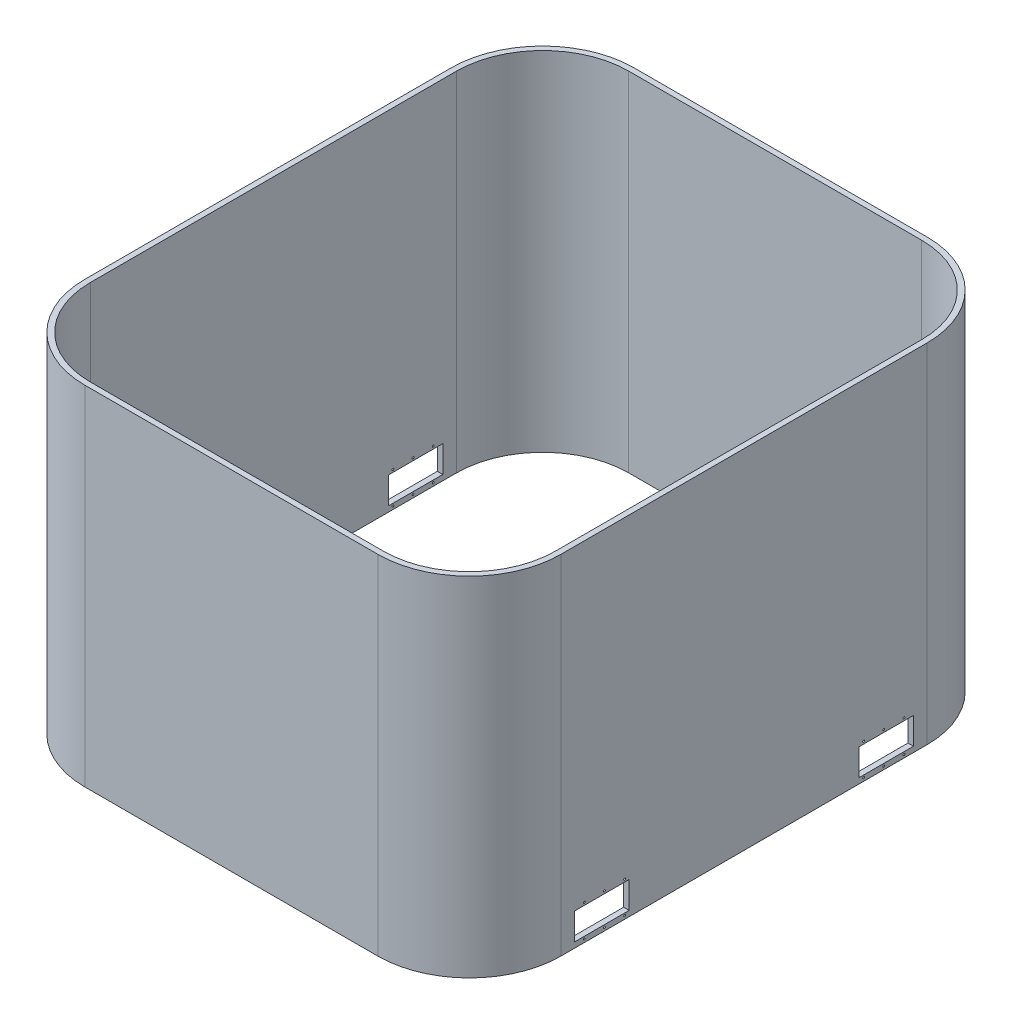
SolidWorks part; units mm, degrees
material "6063-O"
ref_plane "Plano frontal" through (0, 0, 0) normal (0, 0, 1) x (1, 0, 0)
ref_plane "Plano superior" through (0, 0, 0) normal (0, 1, 0) x (1, 0, 0)
ref_plane "Plano direito" through (0, 0, 0) normal (1, 0, 0) x (0, 0, -1)
sketch "Chapa inferior" plane through (0, 0, 0) normal (0, 1, 0) x (1, 0, 0)
  line L1 (-160, 300) -> (160, 300)
  line L2 (-260, 200) -> (-260, -200)
  line L3 (-160, -300) -> (160, -300)
  line L4 (260, 200) -> (260, -200)
  line L5 (-260, 300) -> (260, -300) construction
  line L6 (-260, -300) -> (260, 300) construction
  arc A0 (160, 300) -> (260, 200) centre (160, 200) cw
  arc A1 (160, -300) -> (260, -200) centre (160, -200) ccw
  arc A2 (-260, -200) -> (-160, -300) centre (-160, -200) ccw
  arc A3 (-160, 300) -> (-260, 200) centre (-160, 200) ccw
  point P0 (0, 0)
  dimension "D3" = 100
  dimension "D4" = 100
  dimension "D5" = 100
  dimension "D6" = 100
  dimension "D1" = 520
  dimension "D2" = 600
extrude "ChapaLateral" add sketch "Chapa inferior" along normal blind 380 thin
sketch "Esboço8" plane through (254, 0, 0) normal (-1, 0, 0) x (0, 0, 1)
  line L0 (-200, 380) -> (-200, 0) construction
  line L1 (-185, 6) -> (-125.5, 6)
  line L2 (-185, 6) -> (-185, 35.2)
  line L3 (-185, 35.2) -> (-125.5, 35.2)
  line L4 (-125.5, 6) -> (-125.5, 35.2)
  line L5 (-185, 6) -> (-125.5, 35.2) construction
  line L6 (-185, 35.2) -> (-125.5, 6) construction
  line L7 (200, 0) -> (-200, 0) construction
  point P0 (-155.25, 20.6)
  dimension "D1" = 59.5
  dimension "D2" = 15
  dimension "D3" = 29.2
  dimension "D4" = 6
sketch "Esboço10" plane through (254, 0, 0) normal (-1, 0, 0) x (0, 0, 1)
  line L1 (125.5, 6) -> (185, 6)
  line L2 (125.5, 6) -> (125.5, 35.2)
  line L3 (125.5, 35.2) -> (185, 35.2)
  line L4 (185, 6) -> (185, 35.2)
  line L5 (125.5, 6) -> (185, 35.2) construction
  line L6 (125.5, 35.2) -> (185, 6) construction
  line L8 (200, 380) -> (200, 0) construction
  line L9 (200, 0) -> (-200, 0) construction
  point P0 (155.25, 20.6)
  dimension "D1" = 59.5
  dimension "D2" = 15
  dimension "D3" = 29.2
  dimension "D4" = 6
extrude "MotorTraseiro" cut sketch "Esboço8" against normal through all both and the other way through all
extrude "MotorFrontal" cut sketch "Esboço10" against normal through all both and the other way through all
sketch "Esboço15" plane through (-260, 0, 0) normal (-1, 0, 0) x (0, 0, 1)
  line L1 (185, 6) -> (185, 35.2) construction
  line L2 (185, 35.2) -> (125.5, 35.2) construction
  line L3 (125.5, 35.2) -> (125.5, 6) construction
  line L7 (0, 0) -> (0, 380) construction
  line L8 (-200, 0) -> (200, 0) construction
  line L9 (-200, 380) -> (200, 380) construction
  circle A0 centre (174.5, 38) radius 1.025
  circle A1 centre (152.5, 38) radius 1.025
  circle A2 centre (130.5, 38) radius 1.025
  circle A3 centre (152.5, 3.4) radius 1.025
  circle A4 centre (130.5, 3.4) radius 1.025
  circle A5 centre (174.5, 3.4) radius 1.025
  circle A12 centre (-174.5, 3.4) radius 1.025
  circle A13 centre (-130.5, 3.4) radius 1.025
  circle A14 centre (-152.5, 3.4) radius 1.025
  circle A15 centre (-130.5, 38) radius 1.025
  circle A16 centre (-152.5, 38) radius 1.025
  circle A17 centre (-174.5, 38) radius 1.025
  dimension "D1" = 10.5
  dimension "D2" = 2.8
  dimension "D3" = 3
  dimension "D5" = 5
  dimension "D4" = 2
extrude "FurosDynamixel" cut sketch "Esboço15" against normal through all both and the other way through all
